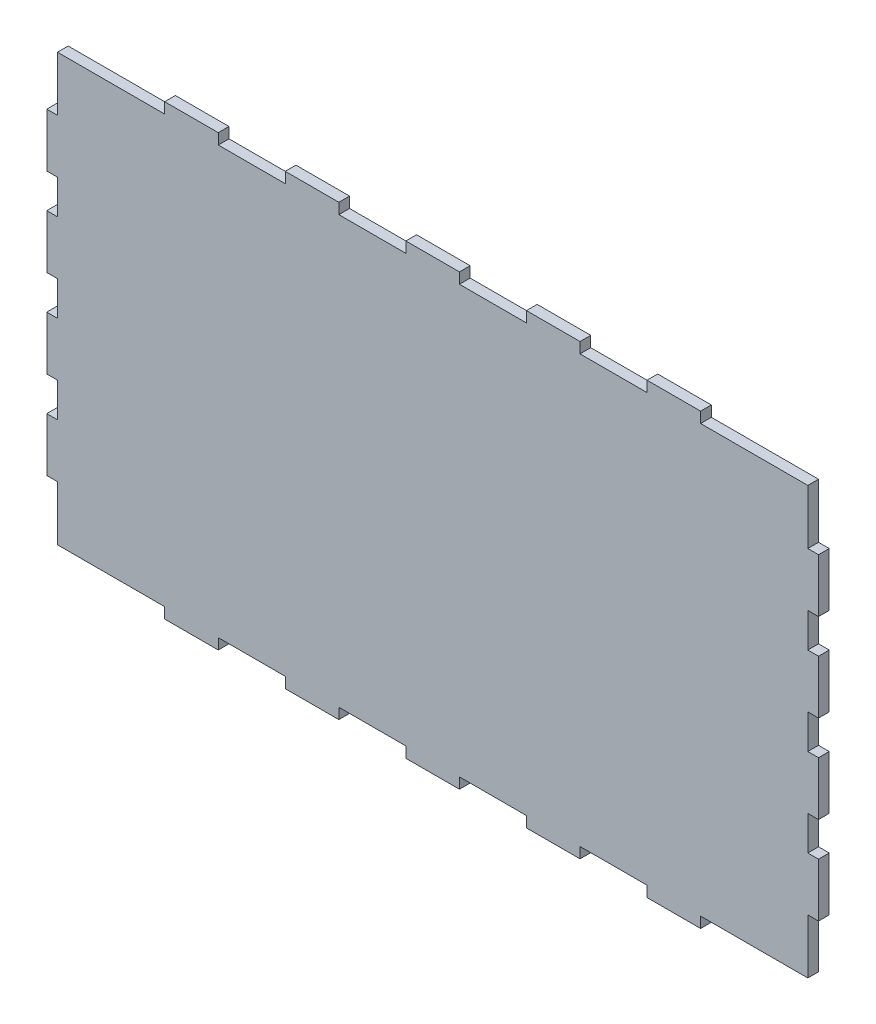
SolidWorks part; units mm, degrees
ref_plane "Front Plane" through (0, 0, 0) normal (0, 0, 1) x (1, 0, 0)
ref_plane "Top Plane" through (0, 0, 0) normal (0, 1, 0) x (1, 0, 0)
ref_plane "Right Plane" through (0, 0, 0) normal (1, 0, 0) x (0, 0, -1)
sketch "Sketch1" plane through (0, 0, 0) normal (0, 0, 1) x (1, 0, 0)
  line L1 (-175, -99.5) -> (175, -99.5)
  line L2 (-175, -99.5) -> (-175, 99.5)
  line L3 (-175, 99.5) -> (175, 99.5)
  line L4 (175, -99.5) -> (175, 99.5)
  line L5 (-175, -99.5) -> (175, 99.5) construction
  line L6 (-175, 99.5) -> (175, -99.5) construction
  point P0 (0, 0)
  dimension "D1" = 350
  dimension "D2" = 199
extrude "Boss-Extrude1" add sketch "Sketch1" along normal blind 5
sketch "Sketch2" plane through (175, 0, 0) normal (1, 0, 0) x (0, 0, -1)
  line L0 (-5, -99.5) -> (-5, 99.5) construction
  line L1 (-5, 74) -> (0, 74)
  line L2 (-5, 74) -> (-5, 49)
  line L3 (-5, 49) -> (0, 49)
  line L4 (0, 74) -> (0, 49)
  line L5 (0, -99.5) -> (0, 99.5) construction
  line L7 (-5, 33) -> (0, 33)
  line L8 (-5, 33) -> (-5, 8)
  line L9 (-5, 8) -> (0, 8)
  line L10 (0, 33) -> (0, 8)
  line L11 (-5, -8) -> (0, -8)
  line L12 (-5, -8) -> (-5, -33)
  line L13 (-5, -33) -> (0, -33)
  line L14 (0, -8) -> (0, -33)
  line L15 (-5, -49) -> (0, -49)
  line L16 (-5, -49) -> (-5, -74)
  line L17 (-5, -74) -> (0, -74)
  line L18 (0, -49) -> (0, -74)
  line L20 (-5, -99.5) -> (0, -99.5) construction
  dimension "D1" = 25
  dimension "D2" = 25
  dimension "D3" = 25
  dimension "D4" = 25
  dimension "D5" = 16
  dimension "D6" = 16
  dimension "D7" = 16
  dimension "D8" = 25.5
extrude "Boss-Extrude2" add sketch "Sketch2" along normal blind 5
mirror "Mirror1" about plane through (0, 0, 0) normal (1, 0, 0) of "Boss-Extrude2"
sketch "Sketch3" plane through (0, 99.5, 0) normal (0, 1, 0) x (1, 0, 0)
  line L0 (175, 0) -> (-175, 0) construction
  line L1 (-125, 0) -> (-100, 0)
  line L2 (-125, 0) -> (-125, -5)
  line L3 (-125, -5) -> (-100, -5)
  line L4 (-100, 0) -> (-100, -5)
  line L5 (175, -5) -> (-175, -5) construction
  line L7 (-68.75, 0) -> (-43.75, 0)
  line L8 (-68.75, 0) -> (-68.75, -5)
  line L9 (-68.75, -5) -> (-43.75, -5)
  line L10 (-43.75, 0) -> (-43.75, -5)
  line L11 (-12.5, 0) -> (12.5, 0)
  line L12 (-12.5, 0) -> (-12.5, -5)
  line L13 (-12.5, -5) -> (12.5, -5)
  line L14 (12.5, 0) -> (12.5, -5)
  line L15 (43.75, 0) -> (68.75, 0)
  line L16 (43.75, 0) -> (43.75, -5)
  line L17 (43.75, -5) -> (68.75, -5)
  line L18 (68.75, 0) -> (68.75, -5)
  line L19 (100, 0) -> (125, 0)
  line L20 (100, 0) -> (100, -5)
  line L21 (100, -5) -> (125, -5)
  line L22 (125, 0) -> (125, -5)
  line L23 (175, -5) -> (175, 0) construction
  dimension "D1" = 25
  dimension "D2" = 25
  dimension "D3" = 25
  dimension "D4" = 25
  dimension "D5" = 25
  dimension "D6" = 31.25
  dimension "D7" = 31.25
  dimension "D8" = 31.25
  dimension "D9" = 31.25
  dimension "D10" = 50
extrude "Boss-Extrude3" add sketch "Sketch3" along normal blind 5
mirror "Mirror2" about plane through (0, 0, 0) normal (0, 1, 0) of "Boss-Extrude3"
